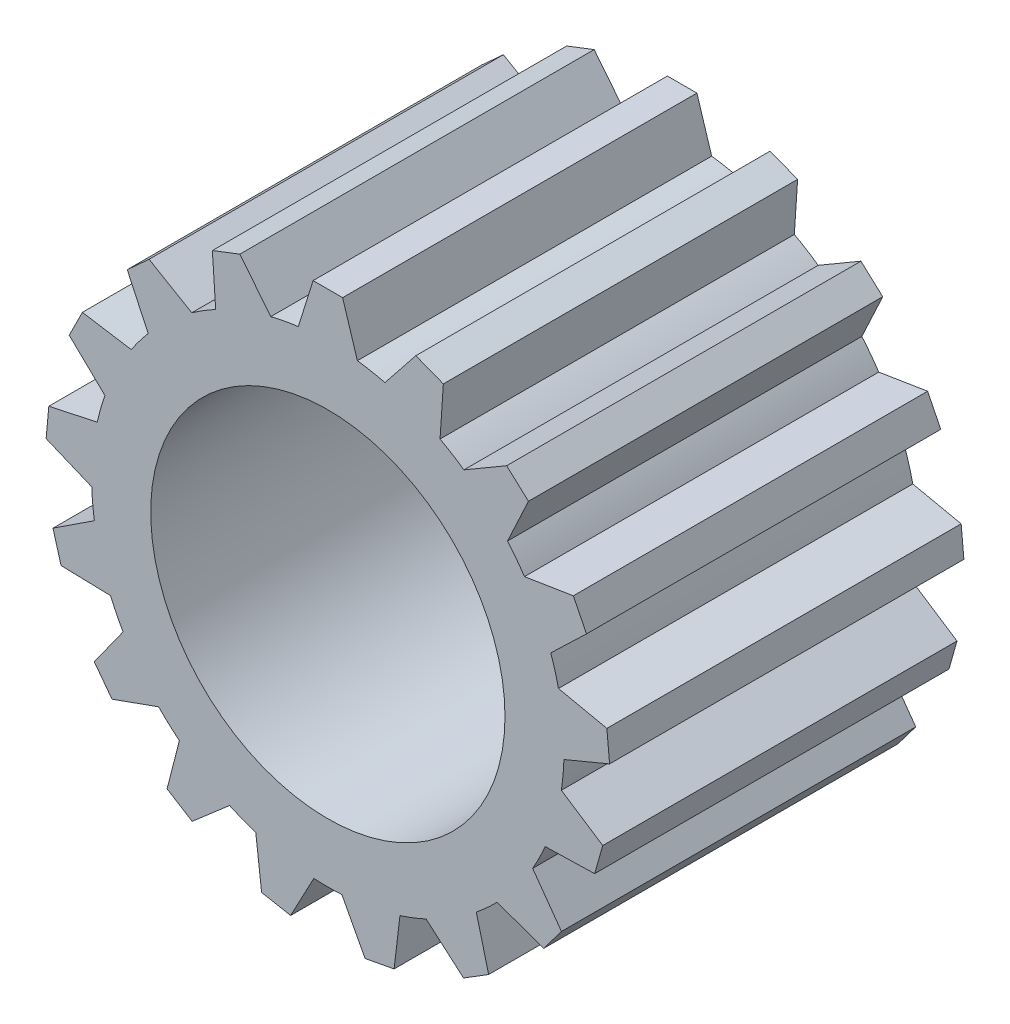
SolidWorks part; units mm, degrees
ref_plane "Front Plane" through (0, 0, 0) normal (0, 0, 1) x (1, 0, 0)
ref_plane "Top Plane" through (0, 0, 0) normal (0, 1, 0) x (1, 0, 0)
ref_plane "Right Plane" through (0, 0, 0) normal (1, 0, 0) x (0, 0, -1)
sketch "Sketch1" plane through (0, 0, 0) normal (0, 0, 1) x (1, 0, 0)
  circle A0 centre (0, 0) radius 4
  dimension "D1" = 8
extrude "Boss-Extrude1" add sketch "Sketch1" along normal blind 6 contours A0
sketch "Sketch3" plane through (0, 0, 0) normal (0, 0, 1) x (1, 0, 0)
  line L0 (0, 0) -> (0, 6.4022) construction
  line L1 (0, 4.7686) -> (0.25, 4.7686)
  line L2 (0.25, 4.7686) -> (0.5, 3.9686)
  line L3 (0.5, 3.9686) -> (-0.5, 3.9686)
  line L4 (-0.5, 3.9686) -> (-0.25, 4.7686)
  line L5 (-0.25, 4.7686) -> (0, 4.7686)
  circle A0 centre (0, 0) radius 4 construction
  dimension "D1" = 0.8
  dimension "D2" = 0.25
  dimension "D3" = 0.25
  dimension "D4" = 1
sketch "Sketch4" plane through (0, 0, 0) normal (0, 1, 0) x (1, 0, 0)
  line L0 (0, -6.6428) -> (0, 0.4527) construction
extrude "Boss-Extrude2" add sketch "Sketch3" along normal blind 6
pattern_circular "CirPattern1" count 17 over 360 about axis through (0, 0, 0) along (0, 0, 1) of "Boss-Extrude2"
sketch "Sketch5" plane through (0, 0, 0) normal (0, 0, 1) x (1, 0, 0)
  circle A0 centre (0, 0) radius 3
  dimension "D1" = 6
extrude "Cut-Extrude1" cut sketch "Sketch5" along normal blind 6
